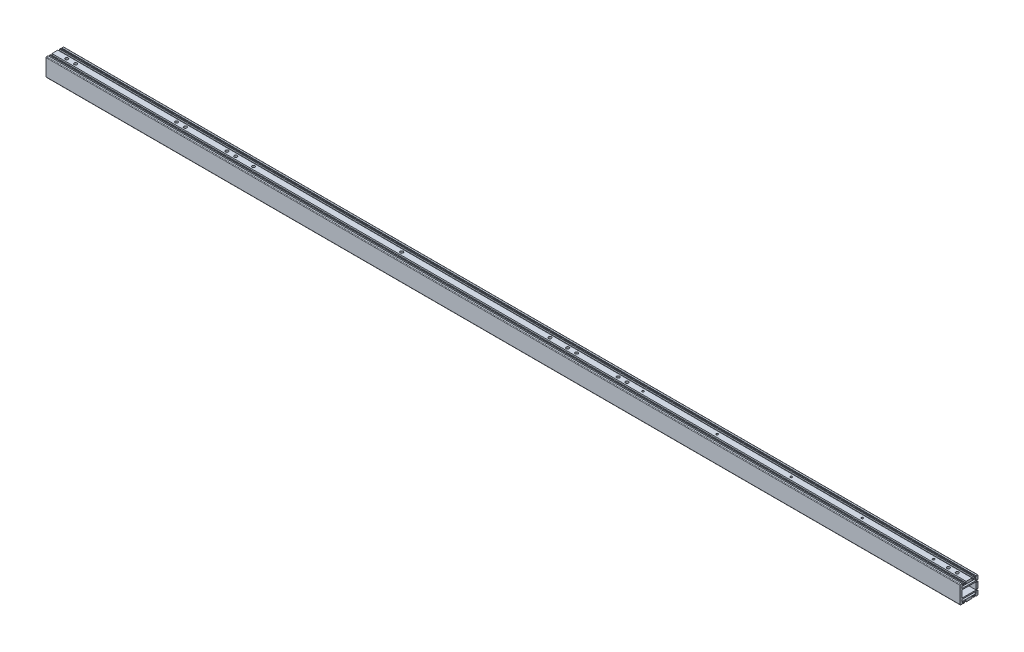
SolidWorks part; units mm, degrees
ref_plane "前视基准面" through (0, 0, 0) normal (0, 0, 1) x (1, 0, 0)
ref_plane "上视基准面" through (0, 0, 0) normal (0, 1, 0) x (1, 0, 0)
ref_plane "右视基准面" through (0, 0, 0) normal (1, 0, 0) x (0, 0, -1)
sketch "草图1" plane through (0, 0, 0) normal (1, 0, 0) x (0, 0, -1)
  line L0 (-15, 15) -> (15, -15) construction
  line L1 (-14, 15) -> (-11.5, 15)
  line L2 (-15, 14) -> (-15, -14)
  line L3 (-14, -15) -> (-11.5, -15)
  line L4 (15, 14) -> (15, 8)
  line L5 (15, 15) -> (-15, -15) construction
  line L6 (-11.5, 15) -> (-11.5, 13.5)
  line L7 (-11.5, 13.5) -> (-11.4, 13.5)
  line L8 (-11, 13.1) -> (-11, 12)
  line L9 (-11, 12) -> (-9.5, 12)
  line L10 (-9.5, 12) -> (-9.5, 15)
  line L11 (-9.5, 15) -> (-8, 15)
  line L12 (-8, 15) -> (-8, 12.5)
  line L13 (-8, 12.5) -> (-5, 12.5)
  line L14 (-5, 12.5) -> (-5, 15)
  line L15 (-5, 15) -> (5, 15)
  line L16 (0, 21.5201) -> (0, -18.309) construction
  line L17 (0, 55) -> (0, -55) construction
  line L18 (5, 12.5) -> (5, 15)
  line L19 (8, 12.5) -> (5, 12.5)
  line L20 (8, 15) -> (8, 12.5)
  line L21 (9.5, 15) -> (8, 15)
  line L22 (9.5, 12) -> (9.5, 15)
  line L23 (11, 12) -> (9.5, 12)
  line L24 (11, 13.1) -> (11, 12)
  line L25 (11.5, 13.5) -> (11.4, 13.5)
  line L26 (11.5, 15) -> (11.5, 13.5)
  line L27 (8, 15) -> (9.5, 15)
  line L28 (11.5, 15) -> (14, 15)
  line L29 (-19.8303, 0) -> (22.13, 0) construction
  line L30 (55, 0) -> (-55, 0) construction
  line L31 (8, -15) -> (9.5, -15)
  line L32 (11.5, -15) -> (11.5, -13.5)
  line L33 (11.5, -13.5) -> (11.4, -13.5)
  line L34 (11, -13.1) -> (11, -12)
  line L35 (11, -12) -> (9.5, -12)
  line L36 (9.5, -12) -> (9.5, -15)
  line L37 (9.5, -15) -> (8, -15)
  line L38 (8, -15) -> (8, -12.5)
  line L39 (8, -12.5) -> (5, -12.5)
  line L40 (5, -12.5) -> (5, -15)
  line L41 (-5, -15) -> (5, -15)
  line L42 (-5, -12.5) -> (-5, -15)
  line L43 (-8, -12.5) -> (-5, -12.5)
  line L44 (-8, -15) -> (-8, -12.5)
  line L45 (-9.5, -15) -> (-8, -15)
  line L46 (-9.5, -12) -> (-9.5, -15)
  line L47 (-11, -12) -> (-9.5, -12)
  line L48 (-11, -13.1) -> (-11, -12)
  line L49 (-11.5, -13.5) -> (-11.4, -13.5)
  line L50 (-11.5, -15) -> (-11.5, -13.5)
  line L51 (-9.5, -15) -> (-8, -15)
  line L52 (-5, -15) -> (5, -15)
  line L53 (8, -15) -> (9.5, -15)
  line L54 (11.5, -15) -> (14, -15)
  line L55 (15, 8) -> (12.5, 8)
  line L56 (12.5, 8) -> (12.5, 5)
  line L57 (12.5, 5) -> (15, 5)
  line L58 (12.5, -5) -> (15, -5)
  line L59 (12.5, -8) -> (12.5, -5)
  line L60 (15, -8) -> (12.5, -8)
  line L61 (15, 5) -> (15, -5)
  line L62 (15, -8) -> (15, -14)
  line L63 (12, -10.5) -> (12, -8.5)
  line L64 (-11.5, 11) -> (11.5, 11)
  line L65 (-12, 10.5) -> (-12, 8.5)
  line L66 (-11.5, 8) -> (11.5, 8)
  line L67 (12, 10.5) -> (12, 8.5)
  line L68 (-11.5, -8) -> (11.5, -8)
  line L69 (-12, -10.5) -> (-12, -8.5)
  line L70 (-11.5, -11) -> (11.5, -11)
  line L72 (-11.75, 6) -> (11.75, 6)
  line L73 (-11.75, 6) -> (-11.75, -6)
  line L74 (-11.75, -6) -> (11.75, -6)
  line L75 (11.75, 6) -> (11.75, -6)
  arc A0 (12, 8.5) -> (11.5, 8) centre (11.5, 8.5) cw
  arc A1 (11.5, 11) -> (12, 10.5) centre (11.5, 10.5) cw
  arc A2 (-11.5, 11) -> (-12, 10.5) centre (-11.5, 10.5) ccw
  arc A3 (-11.5, 8) -> (-12, 8.5) centre (-11.5, 8.5) cw
  arc A4 (-11, -13.1) -> (-11.4, -13.5) centre (-11.4, -13.1) cw
  arc A5 (11.4, -13.5) -> (11, -13.1) centre (11.4, -13.1) cw
  arc A6 (11.4, 13.5) -> (11, 13.1) centre (11.4, 13.1) ccw
  arc A7 (-11, 13.1) -> (-11.4, 13.5) centre (-11.4, 13.1) ccw
  arc A8 (-11.5, -8) -> (-12, -8.5) centre (-11.5, -8.5) ccw
  arc A9 (-11.5, -11) -> (-12, -10.5) centre (-11.5, -10.5) cw
  arc A10 (11.5, -11) -> (12, -10.5) centre (11.5, -10.5) ccw
  arc A11 (12, -8.5) -> (11.5, -8) centre (11.5, -8.5) ccw
  arc A12 (14, 15) -> (15, 14) centre (14, 14) cw
  arc A13 (14, -15) -> (15, -14) centre (14, -14) ccw
  arc A14 (-15, -14) -> (-14, -15) centre (-14, -14) ccw
  arc A15 (-15, 14) -> (-14, 15) centre (-14, 14) cw
  point P69 (12, 11)
  point P72 (-12, 11)
  point P77 (-11, -13.5)
  point P80 (11, -13.5)
  point P83 (11, 13.5)
  point P86 (-11, 13.5)
  point P99 (-12, -11)
  point P100 (12, -11)
  dimension "D17" = 0.5
  dimension "D18" = 0.4
  dimension "D21" = 1
  dimension "D1" = 3.5
  dimension "D2" = 1.5
  dimension "D3" = 0.5
  dimension "D4" = 1.5
  dimension "D5" = 3
  dimension "D6" = 30
  dimension "D7" = 30
  dimension "D8" = 1.5
  dimension "D9" = 2.5
  dimension "D10" = 3
  dimension "D11" = 2.5
  dimension "D12" = 7
  dimension "D13" = 3
  dimension "D14" = 4
  dimension "D15" = 3
  dimension "D16" = 24
  dimension "D19" = 23.5
  dimension "D20" = 12
extrude "凸台-拉伸1" add sketch "草图1" along normal mid plane 1542 contours A15 L2 A14 L3 L50 L49 A4 L48 L47 L46 L45 L44 L43 L42 L41 L40 L39 L38 L31 L36 L35 L34 A5 L33 L32 L54 A13 L62 L60 L59 L58 L61 L57 L56 L55 L4 A12 L28 L26 L25 A6 L24 L23 L22 L21 L20 L19 L18 L15 L14 L13
hole_wizard "M6 螺纹孔1" positions "草图3" profile "草图2" tap size "M6" standard "GB"
sketch "草图3" plane through (0, 15, 0) normal (0, 1, 0) x (-1, 0, 0)
  line L0 (-771, 15) -> (771, 15) construction
  line L1 (-771, 14) -> (-771, 11.5) construction
  point P0 (-751, 0)
  point P1 (-736, 0)
  point P4 (-194, 0)
  point P7 (-179, 0)
  point P10 (-109, 0)
  point P13 (-94, 0)
  point P16 (466, 0)
  point P19 (481, 0)
  point P22 (551, 0)
  point P25 (566, 0)
  point P28 (736, 0)
  point P31 (751, 0)
  dimension "D1" = 15
  dimension "D2" = 20
sketch "草图2" plane through (751, 15, 0) normal (1, 0, 0) x (0, 0, 1)
  line L0 (0, 0) -> (0, 16.5022)
  line L1 (0, 16.5022) -> (2.5, 15)
  line L2 (2.5, 15) -> (2.5, 0)
  line L5 (2.5, 0) -> (0, 0)
  line L10 (0, 16.5022) -> (-2.5, 15) construction
  line L11 (0, -6.35) -> (0, 107.95) construction
  dimension "螺纹孔钻头直径" = 5
  dimension "螺纹孔钻头深度" = 15
  dimension "导头角度" = 118
cosmetic thread "孔螺蚊线1" parameters "D1"=9, "D2"=6
cosmetic thread "孔螺蚊线2" parameters "D1"=9, "D2"=6
cosmetic thread "孔螺蚊线3" parameters "D1"=9, "D2"=6
cosmetic thread "孔螺蚊线4" parameters "D1"=9, "D2"=6
cosmetic thread "孔螺蚊线5" parameters "D1"=9, "D2"=6
cosmetic thread "孔螺蚊线6" parameters "D1"=9, "D2"=6
cosmetic thread "孔螺蚊线7" parameters "D1"=9, "D2"=6
cosmetic thread "孔螺蚊线8" parameters "D1"=9, "D2"=6
cosmetic thread "孔螺蚊线9" parameters "D1"=9, "D2"=6
cosmetic thread "孔螺蚊线10" parameters "D1"=9, "D2"=6
cosmetic thread "孔螺蚊线11" parameters "D1"=9, "D2"=6
cosmetic thread "孔螺蚊线12" parameters "D1"=9, "D2"=6
hole_wizard "M6 螺纹孔2" positions "草图5" profile "草图4" tap size "M6" standard "GB"
sketch "草图5" plane through (0, -15, 0) normal (0, -1, 0) x (1, 0, 0)
  line L0 (-771, 5) -> (-771, -5) construction
  line L1 (771, -15) -> (-771, -15) construction
  point P0 (-751, 0)
  point P1 (-736, 0)
  point P4 (751, 0)
  point P7 (736, 0)
  dimension "D1" = 20
  dimension "D2" = 15
sketch "草图4" plane through (-751, -15, 0) normal (1, 0, 0) x (0, 0, -1)
  line L0 (0, 0) -> (0, 16.5022)
  line L1 (0, 16.5022) -> (2.5, 15)
  line L2 (2.5, 15) -> (2.5, 0)
  line L5 (2.5, 0) -> (0, 0)
  line L10 (0, 16.5022) -> (-2.5, 15) construction
  line L11 (0, -6.35) -> (0, 107.95) construction
  dimension "螺纹孔钻头直径" = 5
  dimension "螺纹孔钻头深度" = 15
  dimension "导头角度" = 118
cosmetic thread "孔螺蚊线13" parameters "D1"=9, "D2"=6
cosmetic thread "孔螺蚊线14" parameters "D1"=9, "D2"=6
cosmetic thread "孔螺蚊线15" parameters "D1"=9, "D2"=6
cosmetic thread "孔螺蚊线16" parameters "D1"=9, "D2"=6
hole_wizard "M4 螺纹孔1" positions "草图7" profile "草图6" tap size "M4" standard "GB"
sketch "草图7" plane through (0, 15, 0) normal (0, 1, 0) x (-1, 0, 0)
  line L0 (-771, 14) -> (-771, 11.5) construction
  line L1 (-771, 15) -> (771, 15) construction
  point P0 (-711, 0)
  point P1 (-591, 0)
  point P3 (-471, 0)
  point P5 (-346, 0)
  point P7 (-221, 0)
  dimension "D1" = 60
  dimension "D2" = 120
  dimension "D3" = 120
  dimension "D4" = 125
  dimension "D5" = 125
  dimension "D6" = 15
sketch "草图6" plane through (711, 15, 0) normal (1, 0, 0) x (0, 0, 1)
  line L0 (0, 0) -> (0, 11.0914)
  line L1 (0, 11.0914) -> (1.65, 10.1)
  line L2 (1.65, 10.1) -> (1.65, 0)
  line L5 (1.65, 0) -> (0, 0)
  line L10 (0, 11.0914) -> (-1.65, 10.1) construction
  line L11 (0, -6.35) -> (0, 107.95) construction
  dimension "螺纹孔钻头直径" = 3.3
  dimension "螺纹孔钻头深度" = 10.1
  dimension "导头角度" = 118
cosmetic thread "孔螺蚊线17" parameters "D1"=8, "D2"=4
cosmetic thread "孔螺蚊线18" parameters "D1"=8, "D2"=4
cosmetic thread "孔螺蚊线19" parameters "D1"=8, "D2"=4
cosmetic thread "孔螺蚊线20" parameters "D1"=8, "D2"=4
cosmetic thread "孔螺蚊线21" parameters "D1"=8, "D2"=4
hole_wizard "M4 螺纹孔2" positions "草图9" profile "草图8" tap size "M4" standard "GB"
sketch "草图9" plane through (0, 0, -15) normal (0, 0, -1) x (-1, 0, 0)
  line L2 (-771, -15) -> (771, -15) construction
  line L4 (771, -8) -> (771, -14) construction
  point P1 (741, 0)
  point P3 (651, 0)
  point P5 (561, 0)
  dimension "D1" = 30
  dimension "D2" = 15
  dimension "D3" = 90
  dimension "D4" = 90
sketch "草图8" plane through (-741, 0, -15) normal (1, 0, 0) x (0, 1, 0)
  line L0 (0, 0) -> (0, 11.0914)
  line L1 (0, 11.0914) -> (1.65, 10.1)
  line L2 (1.65, 10.1) -> (1.65, 0)
  line L5 (1.65, 0) -> (0, 0)
  line L10 (0, 11.0914) -> (-1.65, 10.1) construction
  line L11 (0, -6.35) -> (0, 107.95) construction
  dimension "螺纹孔钻头直径" = 3.3
  dimension "螺纹孔钻头深度" = 10.1
  dimension "导头角度" = 118
cosmetic thread "孔螺蚊线22" parameters "D1"=3.25, "D2"=4
cosmetic thread "孔螺蚊线23" parameters "D1"=3.25, "D2"=4
cosmetic thread "孔螺蚊线24" parameters "D1"=3.25, "D2"=4
hole_wizard "M6 螺纹孔3" positions "草图11" profile "草图10" tap size "M6" standard "GB"
sketch "草图11" plane through (0, 15, 0) normal (0, 1, 0) x (-1, 0, 0)
  line L0 (-771, -15) -> (771, -15) construction
  line L1 (771, -11.5) -> (771, -14) construction
  point P1 (436, 0)
  point P3 (186, 0)
  point P5 (-64, 0)
  dimension "D1" = 15
  dimension "D2" = 335
  dimension "D3" = 250
  dimension "D4" = 250
sketch "草图10" plane through (-436, 15, 0) normal (1, 0, 0) x (0, 0, 1)
  line L0 (0, 0) -> (0, 16.5022)
  line L1 (0, 16.5022) -> (2.5, 15)
  line L2 (2.5, 15) -> (2.5, 0)
  line L5 (2.5, 0) -> (0, 0)
  line L10 (0, 16.5022) -> (-2.5, 15) construction
  line L11 (0, -6.35) -> (0, 107.95) construction
  dimension "螺纹孔钻头直径" = 5
  dimension "螺纹孔钻头深度" = 15
  dimension "导头角度" = 118
cosmetic thread "孔螺蚊线25" parameters "D1"=9, "D2"=6
cosmetic thread "孔螺蚊线26" parameters "D1"=9, "D2"=6
cosmetic thread "孔螺蚊线27" parameters "D1"=9, "D2"=6
